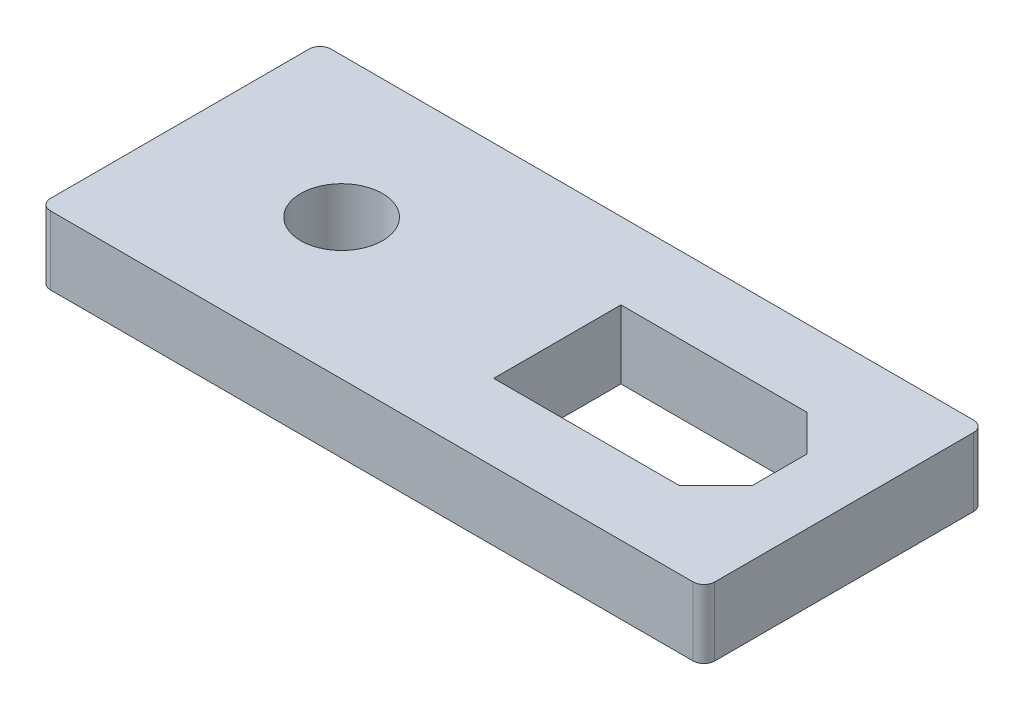
SolidWorks part; units mm, degrees
ref_plane "Front Plane" through (0, 0, 0) normal (0, 0, 1) x (1, 0, 0)
ref_plane "Top Plane" through (0, 0, 0) normal (0, 1, 0) x (1, 0, 0)
ref_plane "Right Plane" through (0, 0, 0) normal (1, 0, 0) x (0, 0, -1)
sketch "Sketch1" plane through (0, 0, 0) normal (0, 1, 0) x (1, 0, 0)
  line L0 (0, 6.5) -> (30.8, 6.5) construction
  line L1 (0, 0) -> (30.8, 0)
  line L2 (0, 0) -> (0, 13)
  line L3 (0, 13) -> (30.8, 13)
  line L4 (30.8, 0) -> (30.8, 13)
  line L5 (15, 13) -> (15, 0) construction
  line L6 (27.75, 7.75) -> (26.1, 9.4) construction
  line L7 (17.55, 3.6) -> (26.1, 3.6) construction
  line L8 (17.55, 3.6) -> (17.55, 9.4) construction
  line L9 (17.55, 9.4) -> (26.1, 9.4) construction
  line L10 (27.75, 5.25) -> (27.75, 7.75) construction
  line L11 (21.9379, 9.4) -> (21.9379, 3.6) construction
  line L12 (17.55, 6.5) -> (27.2, 6.5) construction
  line L13 (27.75, 5.25) -> (26.1, 3.6) construction
  line L14 (27.8, 5.2293) -> (27.8, 7.7707)
  line L15 (27.8, 7.7707) -> (26.1207, 9.45)
  line L16 (17.5, 9.45) -> (26.1207, 9.45)
  line L17 (17.5, 3.55) -> (17.5, 9.45)
  line L18 (17.5, 3.55) -> (26.1207, 3.55)
  line L19 (27.8, 5.2293) -> (26.1207, 3.55)
  circle A0 centre (7.5, 6.5) radius 1.8986
  point P11 (21.9379, 6.5)
  point P12 (27.75, 6.5)
  dimension "D2" = 3.7973
  dimension "D1" = 13
  dimension "D3" = 7.5
  dimension "D4" = 15
  dimension "D5" = 10.2
  dimension "D6" = 5.8
  dimension "D7" = 2.5
  dimension "D8" = 135
  dimension "D10" = 2.5
  dimension "D11" = 3
  dimension "D9" = 0.05
extrude "Boss-Extrude1" add sketch "Sketch1" along normal blind 3.175
fillet "Fillet1" radius 0.5 4 edges at (30.8, 1.5875, -13) (30.8, 1.5875, 0) (0, 1.5875, -13) (0, 1.5875, 0)
